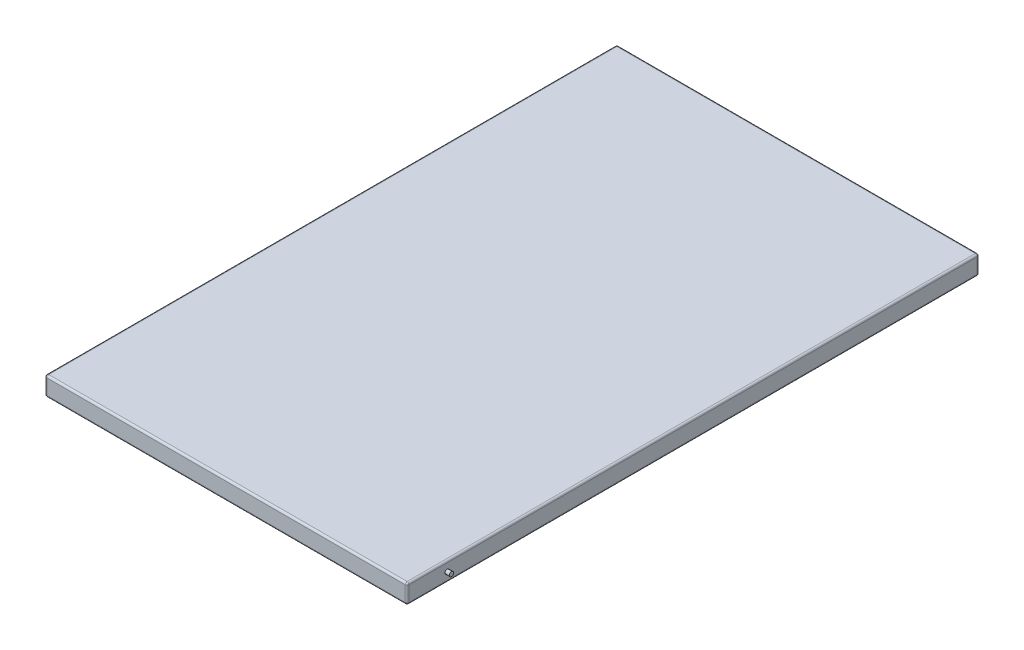
SolidWorks part; units mm, degrees
material "Oak"
ref_plane "Ön Düzlem" through (0, 0, 0) normal (0, 0, 1) x (1, 0, 0)
ref_plane "Üst Düzlem" through (0, 0, 0) normal (0, 1, 0) x (1, 0, 0)
ref_plane "Sağ Düzlem" through (0, 0, 0) normal (1, 0, 0) x (0, 0, -1)
sketch "Sketch1" plane through (0, 0, 0) normal (0, 0, 1) x (1, 0, 0)
  line L0 (-190, 0) -> (190, 0)
  line L1 (190, 0) -> (190, 20)
  line L2 (190, 20) -> (-190, 20)
  line L3 (-190, 20) -> (-190, 0)
  dimension "D1" = 380
  dimension "D2" = 20
  dimension "D3" = 190
extrude "Boss-Extrude1" add sketch "Sketch1" against normal blind 600
fillet "Fillet1" radius 2 12 edges at (190, 10, -600) (0, 0, -600) (-190, 10, -600) (0, 20, -600) (-190, 0, -300) (-190, 20, -300) (-190, 10, 0) (0, 20, 0) (0, 0, 0) (190, 0, -300) (190, 20, -300) (190, 10, 0)
sketch "Sketch3" plane through (190, 0, 0) normal (1, 0, 0) x (0, 0, -1)
  line L0 (2, 18) -> (2, 2) construction
  line L1 (2, 18) -> (2, 2) construction
  circle A0 centre (42, 10) radius 2.25
  point P4 (2, 10)
  dimension "D1" = 4.5
  dimension "D2" = 40
extrude "Boss-Extrude3" add sketch "Sketch3" along normal blind 4.5
